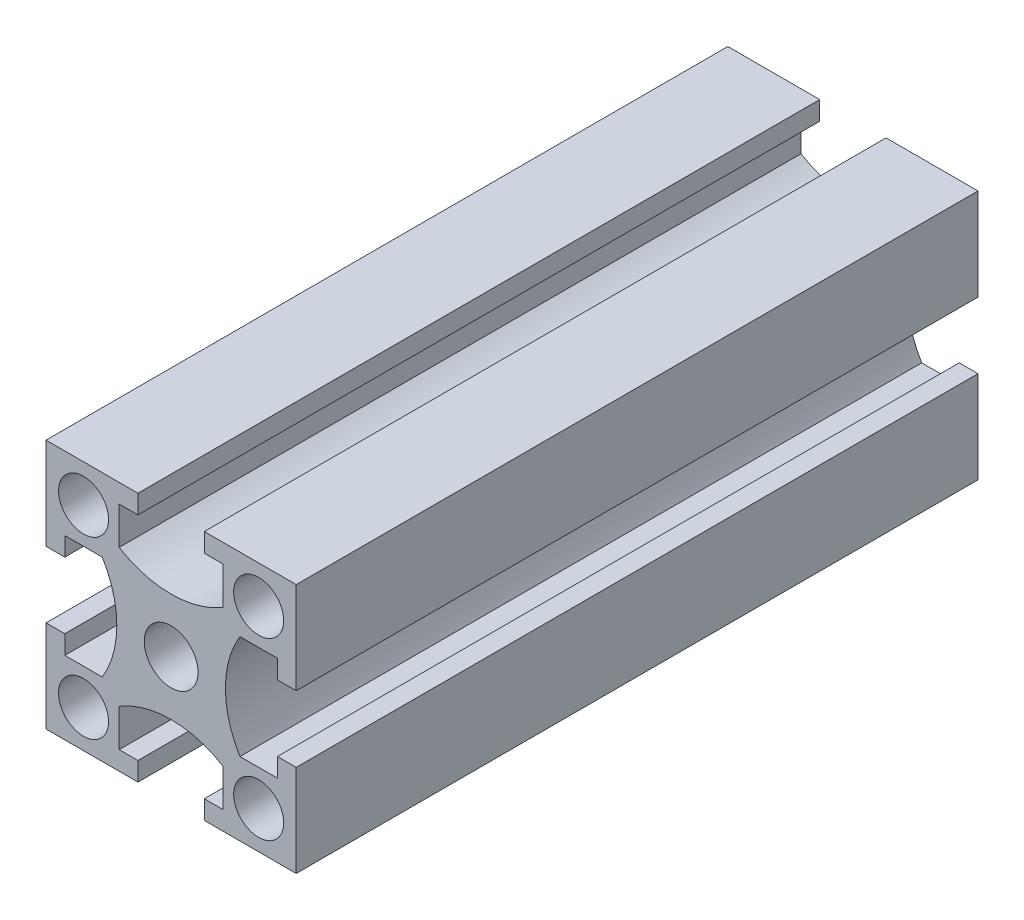
SolidWorks part; units mm, degrees
material "6061-T6 (SS)"
ref_plane "정면" through (0, 0, 0) normal (0, 0, 1) x (1, 0, 0)
ref_plane "윗면" through (0, 0, 0) normal (0, 1, 0) x (1, 0, 0)
ref_plane "우측면" through (0, 0, 0) normal (1, 0, 0) x (0, 0, -1)
sketch "스케치1" plane through (0, 0, 0) normal (0, 0, 1) x (1, 0, 0)
  line L1 (-10, 10) -> (10, 10)
  line L2 (-10, 10) -> (-10, -10)
  line L3 (-10, -10) -> (10, -10)
  line L4 (10, 10) -> (10, -10)
  line L5 (-10, 10) -> (10, -10) construction
  line L6 (-10, -10) -> (10, 10) construction
  point P0 (0, 0)
  dimension "D1" = 20
  dimension "D2" = 20
extrude "보스-돌출1" add sketch "스케치1" along normal blind 54.5
sketch "스케치2" plane through (0, 0, 54.5) normal (0, 0, 1) x (1, 0, 0)
  line L0 (-2.65, 10) -> (-2.65, 8.5)
  line L1 (10, 10) -> (-10, 10) construction
  line L2 (-2.65, 8.5) -> (-4.15, 8.5)
  line L3 (-4.15, 8.5) -> (-4.15, 5.5)
  line L4 (-2.65, 10) -> (2.65, 10)
  line L5 (2.65, 10) -> (2.65, 8.5)
  line L6 (2.65, 8.5) -> (4.15, 8.5)
  line L7 (4.15, 8.5) -> (4.15, 5.5)
  line L8 (10, 2.65) -> (8.5, 2.65)
  line L9 (8.5, 2.65) -> (8.5, 4.15)
  line L10 (8.5, 4.15) -> (5.5, 4.15)
  line L11 (10, 2.65) -> (10, -2.65)
  line L12 (10, -2.65) -> (8.5, -2.65)
  line L13 (8.5, -2.65) -> (8.5, -4.15)
  line L14 (8.5, -4.15) -> (5.5, -4.15)
  line L15 (2.65, -10) -> (2.65, -8.5)
  line L16 (2.65, -8.5) -> (4.15, -8.5)
  line L17 (4.15, -8.5) -> (4.15, -5.5)
  line L18 (2.65, -10) -> (-2.65, -10)
  line L19 (-2.65, -10) -> (-2.65, -8.5)
  line L20 (-2.65, -8.5) -> (-4.15, -8.5)
  line L21 (-4.15, -8.5) -> (-4.15, -5.5)
  line L22 (-10, -2.65) -> (-8.5, -2.65)
  line L23 (-8.5, -2.65) -> (-8.5, -4.15)
  line L24 (-8.5, -4.15) -> (-5.5, -4.15)
  line L25 (-10, -2.65) -> (-10, 2.65)
  line L26 (-10, 2.65) -> (-8.5, 2.65)
  line L27 (-8.5, 2.65) -> (-8.5, 4.15)
  line L28 (-8.5, 4.15) -> (-5.5, 4.15)
  arc A1 (-4.15, 5.5) -> (4.15, 5.5) centre (0, 12.3394) ccw
  arc A2 (5.5, 4.15) -> (5.5, -4.15) centre (12.3394, 0) ccw
  arc A3 (4.15, -5.5) -> (-4.15, -5.5) centre (0, -12.3394) ccw
  arc A4 (-5.5, -4.15) -> (-5.5, 4.15) centre (-12.3394, 0) ccw
  circle A5 centre (0, 0) radius 2.15
  circle A6 centre (-7, 7) radius 2
  circle A7 centre (7, 7) radius 2
  circle A8 centre (7, -7) radius 2
  circle A9 centre (-7, -7) radius 2
  point P4 (-2.65, 9.25)
  point P43 (0, 0)
  dimension "D2" = 1.5
  dimension "D8" = 4.3
  dimension "D9" = 4
  dimension "D10" = 4
  dimension "D11" = 4
  dimension "D12" = 4
  dimension "D21" = 8
  dimension "D1" = 5.3
  dimension "D3" = 8.3
  dimension "D4" = 4.15
  dimension "D5" = 2.65
  dimension "D6" = 4
  dimension "D7" = 3
  dimension "D13" = 14
  dimension "D14" = 7
  dimension "D15" = 7
  dimension "D16" = 7
  dimension "D17" = 14
  dimension "D18" = 7
  dimension "D19" = 7
  dimension "D20" = 7
extrude "컷-돌출1" cut sketch "스케치2" against normal blind 315.5
